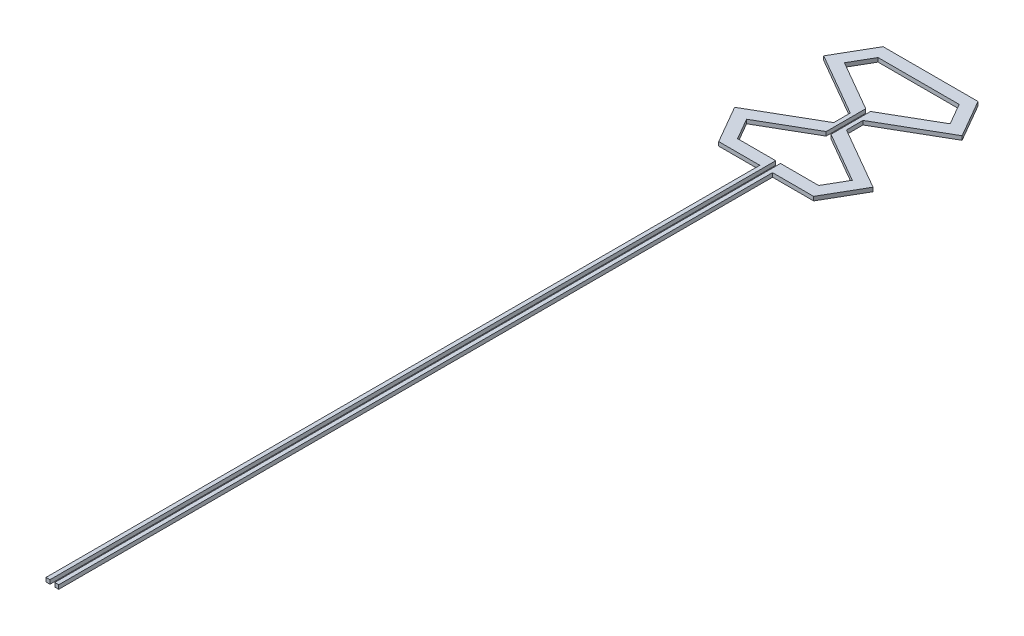
SolidWorks part; units mm, degrees
ref_plane "前视基准面" through (0, 0, 0) normal (0, 0, 1) x (1, 0, 0)
ref_plane "上视基准面" through (0, 0, 0) normal (0, 1, 0) x (1, 0, 0)
ref_plane "右视基准面" through (0, 0, 0) normal (1, 0, 0) x (0, 0, -1)
sketch "草图1" plane through (0, 0, 0) normal (0, 1, 0) x (1, 0, 0)
  line L0 (-18.75, 10.8253) -> (0, 0) construction
  line L1 (18.75, 10.8253) -> (12.5, 21.6506) construction
  line L2 (12.5, 21.6506) -> (-12.5, 21.6506) construction
  line L3 (-12.5, 21.6506) -> (-18.75, 10.8253) construction
  line L4 (11.9226, 20.6506) -> (-11.9226, 20.6506)
  line L5 (-11.9226, 20.6506) -> (-17.384, 11.1913)
  line L6 (-17.384, 11.1913) -> (0, 1.1547)
  line L7 (0, 0) -> (18.75, 10.8253) construction
  line L8 (0, 1.1547) -> (17.384, 11.1913)
  line L9 (-18.75, -10.8253) -> (-12.5, -21.6506) [skipped]
  line L10 (0, -21.6506) -> (12.5, -21.6506) [skipped]
  line L11 (18.75, -10.8253) -> (25, 0) [skipped]
  line L12 (17.384, 11.1913) -> (11.9226, 20.6506)
  line L13 (10.1906, 17.6506) -> (-10.1906, 17.6506)
  line L14 (-10.1906, 17.6506) -> (-13.2859, 12.2894)
  line L15 (-13.2859, 12.2894) -> (0, 4.6188)
  line L16 (0, 4.6188) -> (13.2859, 12.2894)
  line L17 (13.2859, 12.2894) -> (10.1906, 17.6506)
  line L18 (0, -1.1547) -> (-17.384, -11.1913)
  line L19 (0, -4.6188) -> (-13.2859, -12.2894)
  line L20 (-13.2859, -12.2894) -> (-10.1906, -17.6506)
  line L21 (-17.384, -11.1913) -> (-11.9226, -20.6506)
  line L22 (-11.9226, -20.6506) -> (11.9226, -20.6506)
  line L23 (-10.1906, -17.6506) -> (10.1906, -17.6506)
  line L24 (10.1906, -17.6506) -> (13.2859, -12.2894)
  line L25 (11.9226, -20.6506) -> (17.384, -11.1913)
  line L26 (17.384, -11.1913) -> (0, -1.1547)
  line L27 (13.2859, -12.2894) -> (0, -4.6188)
  circle A0 centre (0, 0) radius 21.6506 construction
  point P36 (0, 0)
  dimension "D1" = 25
  dimension "D2" = 1
  dimension "D3" = 3
  dimension "D4" = 2
extrude "凸台-拉伸1" add sketch "草图1" along normal blind 1
sketch "草图2" plane through (0, 0, 0) normal (0, 1, 0) x (1, 0, 0)
  line L0 (-0.6002, 12.8812) -> (-0.6002, -22.1188)
  line L1 (-0.6002, 12.8812) -> (0.6002, 12.8812)
  line L2 (-0.6002, -22.1188) -> (0.6002, -22.1188)
  line L3 (0.6002, 12.8812) -> (0.6002, -22.1188)
  line L4 (-0.6002, 12.8812) -> (0.6002, -22.1188) construction
  line L5 (-0.6002, -22.1188) -> (0.6002, 12.8812) construction
  point P0 (0, 0)
  point P1 (0, -4.6188)
  dimension "D1" = 1.2005
  dimension "D2" = 35
extrude "切除-拉伸1" cut sketch "草图2" against normal blind 2 and the other way blind 2
sketch "草图3" plane through (0, 0, 0) normal (0, 1, 0) x (1, 0, 0)
  line L0 (-0.6002, -20.6506) -> (-1.6002, -20.6506)
  line L1 (-0.6002, -20.6506) -> (-0.6002, -200)
  line L2 (-1.6002, -20.6506) -> (-1.6002, -200)
  line L3 (-0.6002, -200) -> (-1.6002, -200)
  line L4 (-11.9226, -20.6506) -> (-0.6002, -20.6506) construction
  line L5 (0.6002, -20.6506) -> (1.6002, -20.6506)
  line L6 (0.6002, -20.6506) -> (0.6002, -200)
  line L7 (1.6002, -20.6506) -> (1.6002, -200)
  line L8 (0.6002, -200) -> (1.6002, -200)
  line L9 (0.6002, -20.6506) -> (11.9226, -20.6506) construction
  line L10 (-0.6002, -1.5013) -> (-0.6002, 1.5013)
  line L11 (0.6002, -1.5013) -> (0.6002, 1.5013)
  line L12 (-1.6002, -2.0786) -> (-1.6002, 2.0786)
  line L13 (-0.6002, -1.5013) -> (-17.384, -11.1913) construction
  line L14 (-17.384, 11.1913) -> (-0.6002, 1.5013) construction
  line L15 (-1.6002, 2.0786) -> (-0.6002, 1.5013)
  line L16 (-1.6002, -2.0786) -> (-0.6002, -1.5013)
  line L17 (1.6002, -2.0786) -> (1.6002, 2.0786)
  line L18 (17.384, -11.1913) -> (0.6002, -1.5013) construction
  line L19 (0.6002, 1.5013) -> (17.384, 11.1913) construction
  line L20 (1.6002, 2.0786) -> (0.6002, 1.5013)
  line L21 (1.6002, -2.0786) -> (0.6002, -1.5013)
  dimension "D1" = 1
  dimension "D2" = 200
extrude "凸台-拉伸2" add sketch "草图3" along normal blind 1
